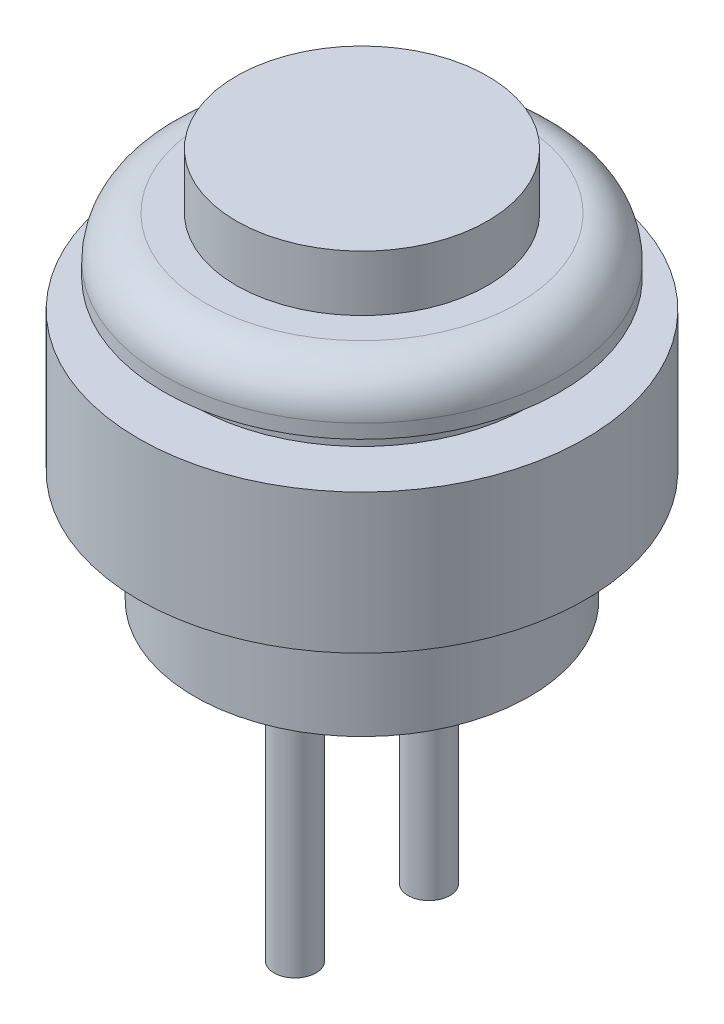
SolidWorks part; units mm, degrees
ref_plane "前视基准面" through (0, 0, 0) normal (0, 0, 1) x (1, 0, 0)
ref_plane "上视基准面" through (0, 0, 0) normal (0, 1, 0) x (1, 0, 0)
ref_plane "右视基准面" through (0, 0, 0) normal (1, 0, 0) x (0, 0, -1)
sketch "草图1" plane through (0, 0, 0) normal (0, 1, 0) x (1, 0, 0)
  circle A0 centre (0, 0) radius 7.1
  dimension "D1" = 14.2
extrude "拉伸1" add sketch "草图1" along normal blind 2
fillet "圆角1" radius 1.5 1 edges at (0, 2, 7.1)
sketch "草图2" plane through (0, 2, 0) normal (0, 1, 0) x (-1, 0, 0)
  circle A0 centre (0, 0) radius 4.5
  dimension "D1" = 9
extrude "拉伸2" add sketch "草图2" along normal blind 2
sketch "草图3" plane through (0, 0, 0) normal (0, -1, 0) x (1, 0, 0)
  circle A0 centre (0, 0) radius 6
  dimension "D1" = 12
extrude "拉伸3" add sketch "草图3" along normal blind 10
sketch "草图4" plane through (0, -10, 0) normal (0, -1, 0) x (1, 0, 0)
  line L0 (0, 5.4821) -> (0, -6.0169) construction
  circle A0 centre (0, -2.4) radius 0.75
  circle A1 centre (0, 2.4) radius 0.75
  dimension "D1" = 1.5
  dimension "D2" = 1.5
  dimension "D3" = 2.4
  dimension "D4" = 2.4
extrude "拉伸4" add sketch "草图4" along normal blind 10
ref_plane "基准面1" through (0, -1, 0) normal (0, -1, 0) x (1, 0, 0)
sketch "草图5" plane through (0, -1, 0) normal (0, -1, 0) x (1, 0, 0)
  circle A0 centre (0, 0) radius 6
  circle A1 centre (0, 0) radius 6 construction
  circle A2 centre (0, 0) radius 8
  dimension "D1" = 16
extrude "拉伸5" add sketch "草图5" along normal blind 5
